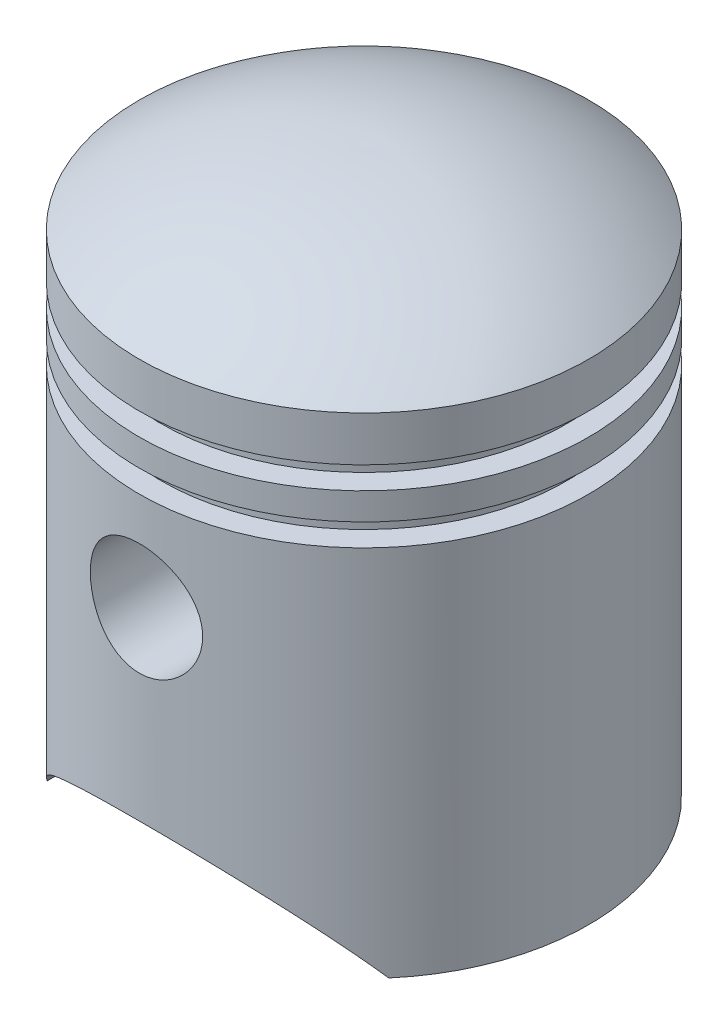
SolidWorks part; units mm, degrees
ref_plane "Front Plane" through (0, 0, 0) normal (0, 0, 1) x (1, 0, 0)
ref_plane "Top Plane" through (0, 0, 0) normal (0, 1, 0) x (1, 0, 0)
ref_plane "Right Plane" through (0, 0, 0) normal (1, 0, 0) x (0, 0, -1)
sketch "Sketch2" plane through (0, 0, 0) normal (0, 0, 1) x (1, 0, 0)
  line L0 (25, 0) -> (25, 41.5)
  line L1 (25, 49.5) -> (22.5, 49.5)
  line L2 (22.5, 49.5) -> (22.5, 47)
  line L3 (22.5, 47) -> (25, 47)
  line L4 (25, 44) -> (22.5, 44)
  line L5 (22.5, 44) -> (22.5, 41.5)
  line L6 (22.5, 41.5) -> (25, 41.5)
  line L7 (25, 49.5) -> (25, 54.5)
  line L8 (25, 44) -> (25, 47)
  line L9 (23, 0) -> (23, 39.5)
  line L10 (20.5, 39.5) -> (23, 39.5)
  line L11 (20.5, 45.5) -> (20.5, 39.5)
  line L12 (20.5, 45.5) -> (20.5, 45.5)
  line L13 (20.5, 45.5) -> (20.5, 45.5)
  line L14 (20.5, 45.5) -> (20.5, 45.5)
  line L15 (20.5, 51.5) -> (20.5, 45.5)
  line L16 (23, 51.5) -> (20.5, 51.5)
  line L17 (23, 51.5) -> (23, 53.4845)
  line L18 (25, 0) -> (23, 0)
  line L20 (0, 62.5) -> (0, 60.4994)
  arc A0 (25, 54.5) -> (0, 62.5) centre (0.9839, 22.5121) ccw
  arc A1 (23, 53.4845) -> (0, 60.4994) centre (0.9839, 22.5121) ccw
  arc A2 (23, 53.4845) -> (0.0492, 60.5006) centre (0.9839, 22.5121) ccw construction
  dimension "D4" = 40
  dimension "D1" = 25
  dimension "D2" = 62.5
  dimension "D3" = 54.5
  dimension "D5" = 5
  dimension "D6" = 2.5
  dimension "D7" = 2.5
  dimension "D8" = 3
  dimension "D9" = 2.5
  dimension "D10" = 2
revolve "Revolve1" add sketch "Sketch2" angle 360 about L20
sketch "Sketch3" plane through (0, 0, 0) normal (0, 0, 1) x (1, 0, 0)
  line L0 (-25, 0) -> (25, 0) construction
  line L1 (0, 30.5) -> (0, 62.5) construction
  line L2 (-19, 0) -> (19, 0)
  circle A0 centre (0, 30.5) radius 6.25
  arc A1 (-19, 0) -> (19, 0) centre (0, -13.05) cw
  point P5 (0, 10)
  dimension "D1" = 12.5
  dimension "D2" = 32
  dimension "D3" = 38
  dimension "D4" = 10
extrude "Cut-Extrude1" cut sketch "Sketch3" against normal through all both and the other way through all
sketch "Sketch4" plane through (0, 0, 0) normal (0, 0, 1) x (1, 0, 0)
  circle A0 centre (0, 30.5) radius 7.25
  circle A1 centre (0, 30.5) radius 6.25
  dimension "D1" = 14.5
  dimension "D2" = 12.5
extrude "Boss-Extrude1" add sketch "Sketch4" along normal up to surface (11.9257 mm away) from offset 12
mirror "Mirror1" about plane through (0, 0, 0) normal (0, 0, 1) of "Boss-Extrude1"
